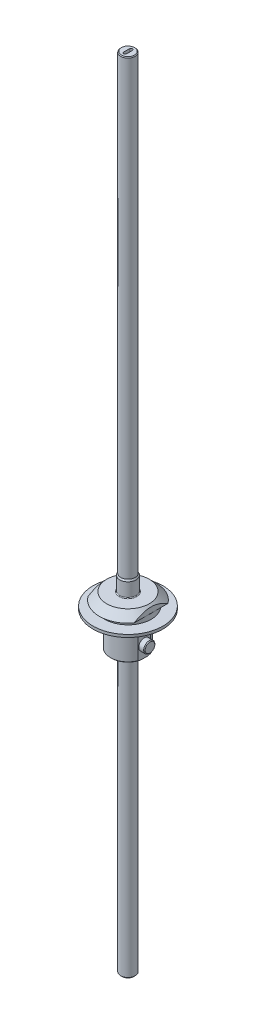
SolidWorks part; units mm, degrees
material "AISI 316 Annealed Stainless Steel Bar (SS)"
ref_plane "Front Plane" through (0, 0, 0) normal (0, 0, 1) x (1, 0, 0)
ref_plane "Top Plane" through (0, 0, 0) normal (0, 1, 0) x (1, 0, 0)
ref_plane "Right Plane" through (0, 0, 0) normal (1, 0, 0) x (0, 0, -1)
sketch "Sketch1" plane through (0, 0, 0) normal (0, 0, 1) x (1, 0, 0)
  line L0 (0, 0) -> (0, 82.4738) construction
  line L1 (0, 82.4738) -> (1.2382, 82.4738)
  line L2 (1.2382, 82.4738) -> (1.2382, 2.5908)
  line L5 (1.2382, 2.5908) -> (3.6322, 2.5908)
  line L6 (3.6322, 2.5908) -> (4.8768, 1.3462)
  line L7 (4.8768, 1.3462) -> (3.9688, 1.3462)
  line L8 (3.9688, 1.3462) -> (3.9688, 0.4572)
  line L9 (3.9688, 0.4572) -> (5.969, 0.4572)
  line L10 (5.969, 0.4572) -> (5.969, 0)
  line L11 (5.969, 0) -> (2.9845, 0)
  line L12 (2.9845, 0) -> (2.9845, -5.842)
  line L13 (2.9845, -5.842) -> (1.2383, -5.842)
  line L14 (1.2383, -5.842) -> (1.2383, -53.8734)
  line L15 (1.2383, -53.8734) -> (0, -53.8734)
  line L16 (0, -53.8734) -> (0, 0) construction
  line L17 (0, 82.4738) -> (0, -53.8734)
  dimension "D3" = 11.938
  dimension "D4" = 9.7536
  dimension "D5" = 7.9375
  dimension "D6" = 0.4572
  dimension "D7" = 2.5908
  dimension "D8" = 0.889
  dimension "D9" = 45
  dimension "D10" = 5.969
  dimension "D11" = 8.4328
  dimension "D12" = 56.4642
  dimension "D13" = 2.4765
  dimension "D15" = 79.883
revolve "Revolve1" add sketch "Sketch1" angle 360 about L17
chamfer "Chamfer1" distance 0.254 angle 45 1 edges at (-1.2382, -53.8734, 0)
sketch "Sketch4" plane through (0, -5.842, 0) normal (0, -1, 0) x (1, 0, 0)
  line L0 (-2.794, 1.0492) -> (-2.794, -1.0492)
  line L1 (2.794, 1.0492) -> (2.794, -1.0492)
  arc A0 (2.794, -1.0492) -> (2.794, 1.0492) centre (0, 0) ccw
  circle A1 centre (0, 0) radius 2.9845
  arc A2 (-2.794, 1.0492) -> (-2.794, -1.0492) centre (0, 0) ccw
  dimension "D2" = 5.588
  dimension "D1" = 0
extrude "Cut-Extrude3" cut sketch "Sketch4" against normal blind 3.81
sketch "Sketch5" plane through (0, 0, 0) normal (1, 0, 0) x (0, 0, -1)
  line L0 (0, -3.81) -> (0, -5.842) construction
  line L1 (-1.2382, -5.842) -> (1.2382, -5.842) construction
  circle A0 centre (0, -3.81) radius 0.9525
  dimension "D1" = 1.905
  dimension "D2" = 2.032
extrude "Boss-Extrude1" add sketch "Sketch5" along normal mid plane 7.5184
sketch "Sketch2" plane through (0, -53.8734, 0) normal (0, -1, 0) x (1, 0, 0)
  line L0 (0, 0.508) -> (0, -0.508) construction
  line L1 (0.254, 0.508) -> (0.254, -0.508)
  line L2 (-0.254, 0.508) -> (-0.254, -0.508)
  arc A0 (0.254, 0.508) -> (-0.254, 0.508) centre (0, 0.508) ccw
  arc A1 (-0.254, -0.508) -> (0.254, -0.508) centre (0, -0.508) ccw
  point P2 (0, 0)
  dimension "D2" = 1.524
  dimension "D1" = 0.508
extrude "Cut-Extrude1" cut sketch "Sketch2" against normal through all
chamfer "Chamfer2" distance 0.127 angle 45 5 edges at (0, -5.842, 2.9845) (0, -5.842, -2.9845) (3.7592, -3.81, -0.9525) (-3.7592, -3.81, -0.9525) (-1.2382, 82.4738, 0)
sketch "Sketch6" plane through (0, 1.3462, 0) normal (0, -1, 0) x (1, 0, 0)
  line L0 (-3.937, -2.8781) -> (-3.937, 2.8781)
  line L1 (3.937, -2.8781) -> (3.937, 2.8781)
  circle A0 centre (0, 0) radius 4.8768 construction
  arc A1 (3.937, -2.8781) -> (3.937, 2.8781) centre (0, 0) ccw
  arc A2 (-3.937, 2.8781) -> (-3.937, -2.8781) centre (0, 0) ccw
  dimension "D1" = 7.874
extrude "Cut-Extrude4" cut sketch "Sketch6" against normal up to next
fillet "Fillet1" radius 0.508 1 edges at (-1.2382, -5.842, 0)
sketch "Sketch7" plane through (0, 0, 0) normal (0, 0, 1) x (1, 0, 0)
  line L0 (1.2382, 5.2788) -> (1.2382, 2.5908)
  line L1 (1.2382, 2.5908) -> (1.2382, 82.3468) construction
  line L2 (1.2382, 2.5908) -> (1.397, 2.5908)
  line L3 (3.6322, 2.5908) -> (-3.6322, 2.5908) construction
  line L4 (1.397, 2.5908) -> (1.397, 5.0038)
  line L5 (1.397, 5.0038) -> (1.2382, 5.2788)
  line L6 (0, 0) -> (0, 2.5908) construction
  line L7 (1.2382, 2.5908) -> (-1.2382, 2.5908) construction
  dimension "D1" = 2.794
  dimension "D2" = 2.413
  dimension "D3" = 30
revolve "Revolve2" add sketch "Sketch7" angle 360 about L6
fillet "Fillet2" radius 0.127 1 edges at (1.397, 2.5908, 0)
